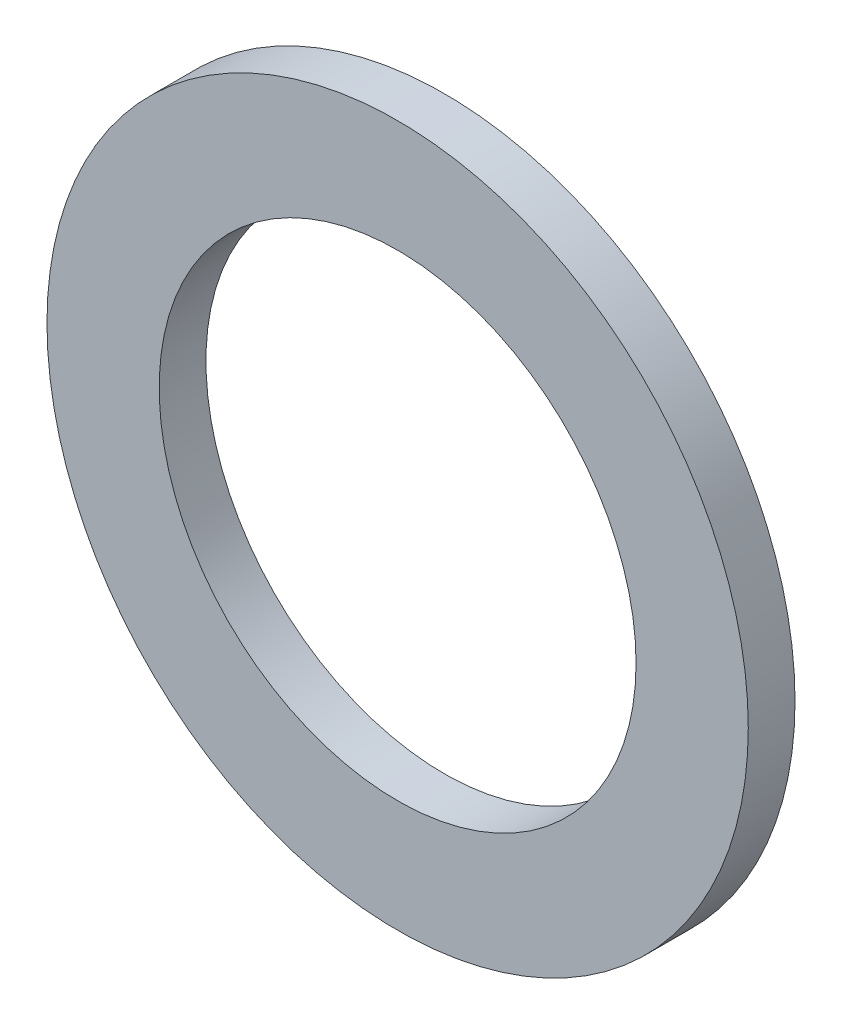
SolidWorks part; units mm, degrees
ref_plane "前视基准面" through (0, 0, 0) normal (0, 0, 1) x (1, 0, 0)
ref_plane "上视基准面" through (0, 0, 0) normal (0, 1, 0) x (1, 0, 0)
ref_plane "右视基准面" through (0, 0, 0) normal (1, 0, 0) x (0, 0, -1)
sketch "草图1" plane through (0, 0, 0) normal (0, 0, 1) x (1, 0, 0)
  circle A0 centre (0, 0) radius 5.1
  circle A1 centre (0, 0) radius 7.5
  dimension "D1" = 10.2
  dimension "D2" = 15
extrude "凸台-拉伸1" add sketch "草图1" along normal blind 1
